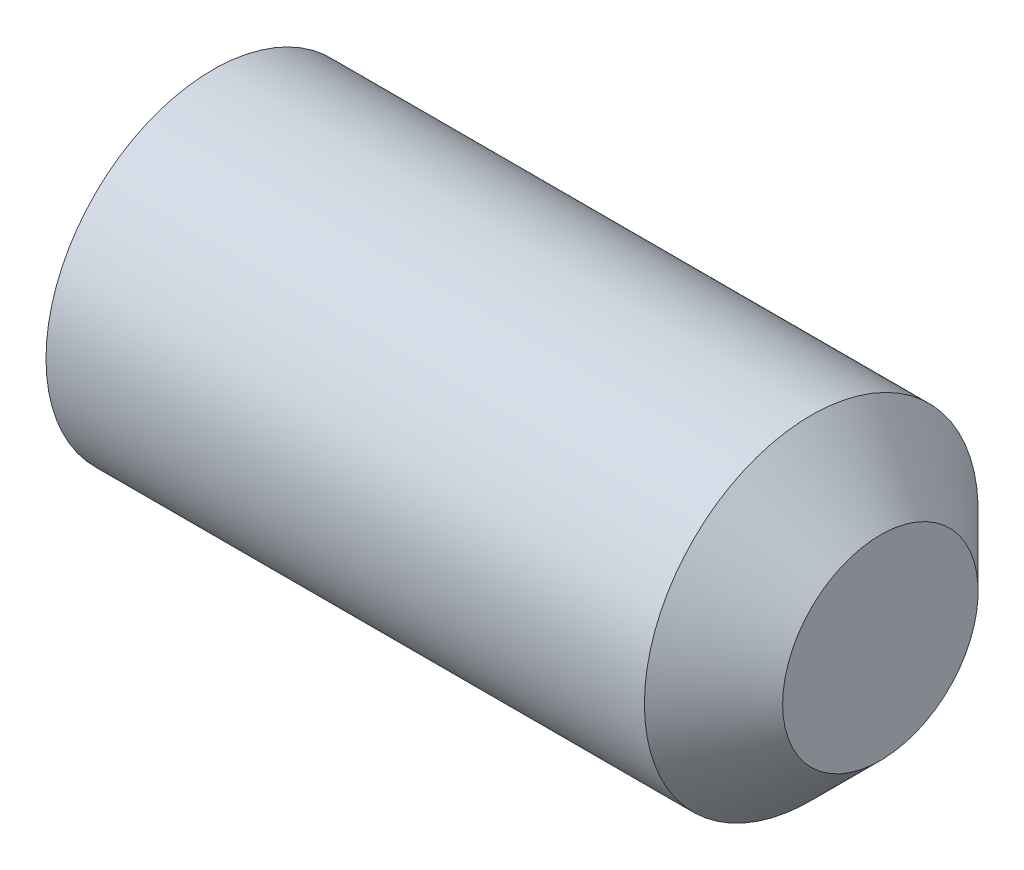
SolidWorks part; units mm, degrees
material "AISI 304"
ref_plane "Front Plane" through (0, 0, 0) normal (0, 0, 1) x (1, 0, 0)
ref_plane "Top Plane" through (0, 0, 0) normal (0, 1, 0) x (1, 0, 0)
ref_plane "Right Plane" through (0, 0, 0) normal (1, 0, 0) x (0, 0, -1)
sketch "Sketch1" plane through (0, 0, 0) normal (0, 0, 1) x (1, 0, 0)
  line L0 (0, 0) -> (105.4919, 0) construction
  line L1 (10, 1.4645) -> (10, 0)
  line L2 (10, 1.4645) -> (8.9645, 2.5)
  line L3 (8.9645, 2.5) -> (0, 2.5)
  line L4 (0, 2.5) -> (0, 0)
  line L5 (0, 0) -> (10, 0)
  dimension "D1" = 5
  dimension "D2" = 10
  dimension "D3" = 45
  dimension "D4" = 90
revolve "Revolve1" add sketch "Sketch1" angle 360 about L0
sketch "Sketch2" plane through (0, 0, 0) normal (-1, 0, 0) x (0, 0, 1)
  line L1 (-0.7217, 1.25) -> (-1.4434, 0)
  line L2 (-1.4434, 0) -> (-0.7217, -1.25)
  line L3 (-0.7217, -1.25) -> (0.7217, -1.25)
  line L4 (0.7217, -1.25) -> (1.4434, 0)
  line L5 (1.4434, 0) -> (0.7217, 1.25)
  line L6 (0.7217, 1.25) -> (-0.7217, 1.25)
  circle A0 centre (0, 0) radius 1.25 construction
  dimension "D1" = 2.5
extrude "Cut-Extrude1" cut sketch "Sketch2" against normal blind 2
